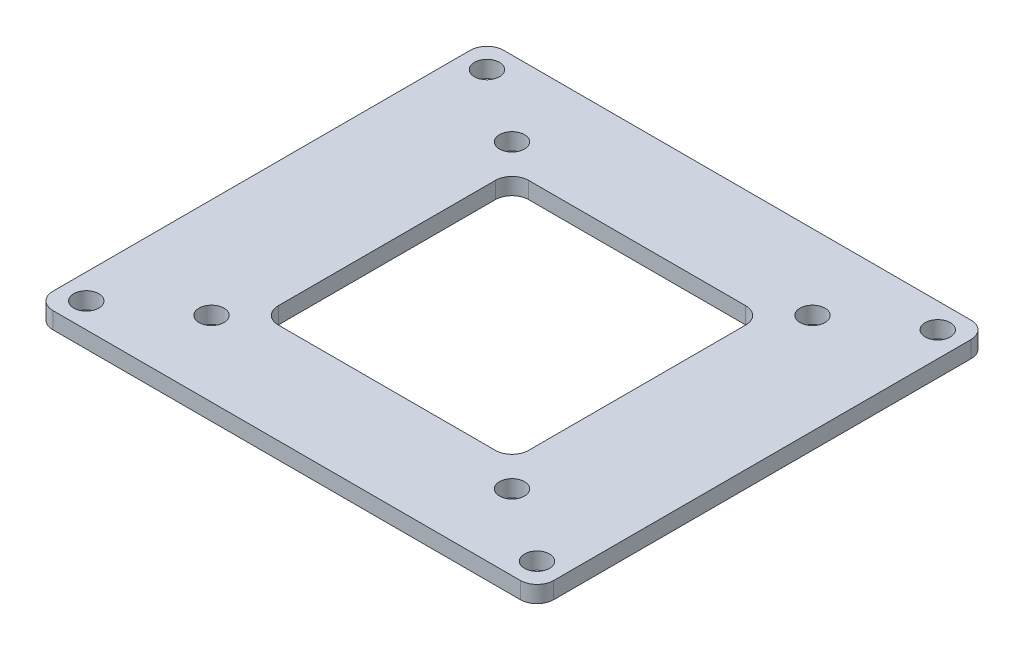
SolidWorks part; units mm, degrees
material "Thornel Mat VMA"
ref_plane "前视基准面" through (0, 0, 0) normal (0, 0, 1) x (1, 0, 0)
ref_plane "上视基准面" through (0, 0, 0) normal (0, 1, 0) x (1, 0, 0)
ref_plane "右视基准面" through (0, 0, 0) normal (1, 0, 0) x (0, 0, -1)
sketch "草图1" plane through (0, 0, 0) normal (0, 1, 0) x (1, 0, 0)
  line L1 (-30, 27) -> (30, 27)
  line L2 (-30, 27) -> (-30, -27)
  line L3 (-30, -27) -> (30, -27)
  line L4 (30, 27) -> (30, -27)
  line L5 (0, -27) -> (0, 27) construction
  line L6 (-30, 0) -> (30, 0) construction
  circle A0 centre (27, 24) radius 1.5
  circle A1 centre (-27, 24) radius 1.5
  circle A2 centre (-27, -24) radius 1.5
  circle A3 centre (27, -24) radius 1.5
  point P0 (0, 0)
  dimension "D1" = 48
  dimension "D2" = 54
  dimension "D3" = 3
  dimension "D4" = 60
  dimension "D5" = 54
extrude "凸台-拉伸1" add sketch "草图1" along normal blind 2
sketch "草图2" plane through (0, 2, 0) normal (0, 1, 0) x (1, 0, 0)
  line L0 (-30, 0) -> (30, 0) construction
  line L1 (-30, 27) -> (-30, -27) construction
  line L2 (30, -27) -> (30, 27) construction
  line L3 (0, 27) -> (0, -27) construction
  line L4 (30, 27) -> (-30, 27) construction
  line L5 (-30, -27) -> (30, -27) construction
  circle A0 centre (18, 18) radius 1.5
  circle A1 centre (-18, 18) radius 1.5
  circle A2 centre (18, -18) radius 1.5
  circle A3 centre (-18, -18) radius 1.5
  dimension "D1" = 36
  dimension "D2" = 36
  dimension "D3" = 3
extrude "切除-拉伸1" cut sketch "草图2" against normal blind 2
fillet "圆角1" radius 2 4 edges at (30, 1, 27) (-30, 1, 27) (30, 1, -27) (-30, 1, -27)
sketch "草图3" plane through (0, 2, 0) normal (0, 1, 0) x (1, 0, 0)
  line L1 (-15, 15) -> (15, 15)
  line L2 (-15, 15) -> (-15, -15)
  line L3 (-15, -15) -> (15, -15)
  line L4 (15, 15) -> (15, -15)
  line L5 (0, -15) -> (0, 15) construction
  line L6 (-15, 0) -> (15, 0) construction
  point P0 (0, 0)
  dimension "D1" = 30
  dimension "D2" = 30
extrude "切除-拉伸2" cut sketch "草图3" against normal blind 2
fillet "圆角2" radius 2 4 edges at (15, 1, 15) (-15, 1, 15) (15, 1, -15) (-15, 1, -15)
